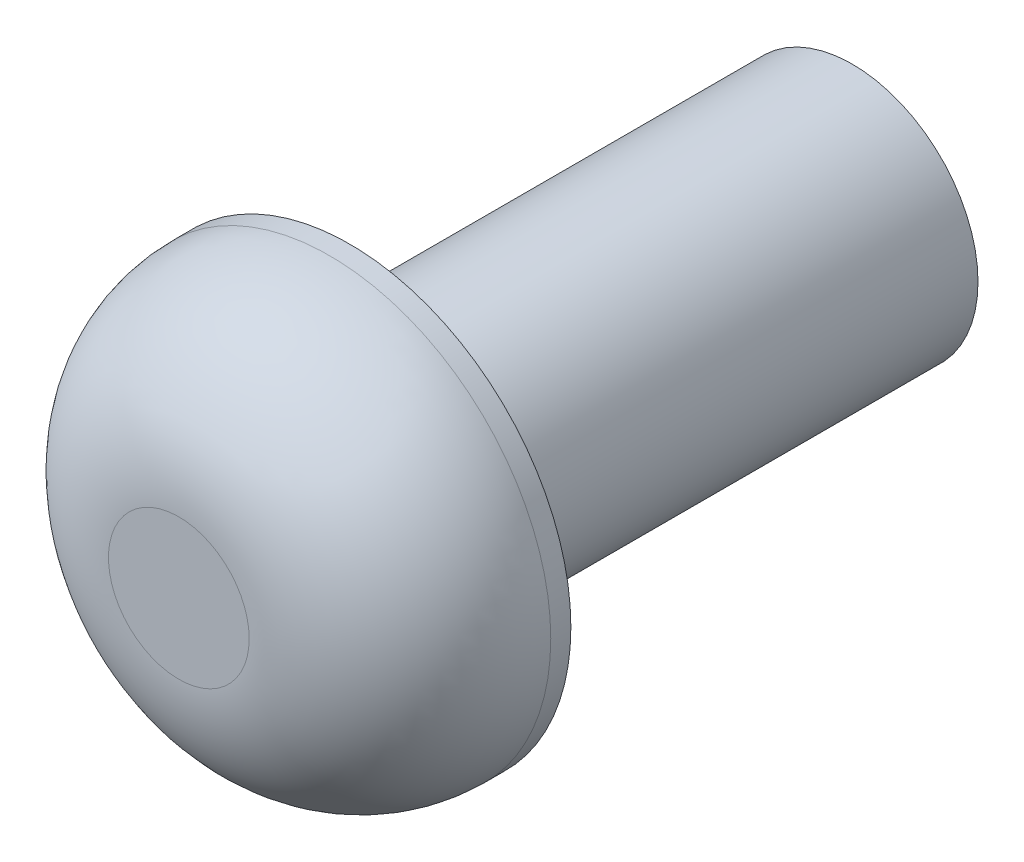
SolidWorks part; units mm, degrees
ref_plane "前视基准面" through (0, 0, 0) normal (0, 0, 1) x (1, 0, 0)
ref_plane "上视基准面" through (0, 0, 0) normal (0, 1, 0) x (1, 0, 0)
ref_plane "右视基准面" through (0, 0, 0) normal (1, 0, 0) x (0, 0, -1)
sketch "草图1" plane through (0, 0, 0) normal (0, 0, 1) x (1, 0, 0)
  circle A0 centre (0, 0) radius 2.5
extrude "凸台-拉伸1" add sketch "草图1" along normal blind 10
sketch "草图2" plane through (0, 0, 10) normal (0, 0, 1) x (1, 0, 0)
  circle A0 centre (0, 0) radius 4.4
extrude "凸台-拉伸2" add sketch "草图2" along normal blind 3.4
fillet "圆角1" radius 3 1 edges at (4.4, 0, 13.4)
